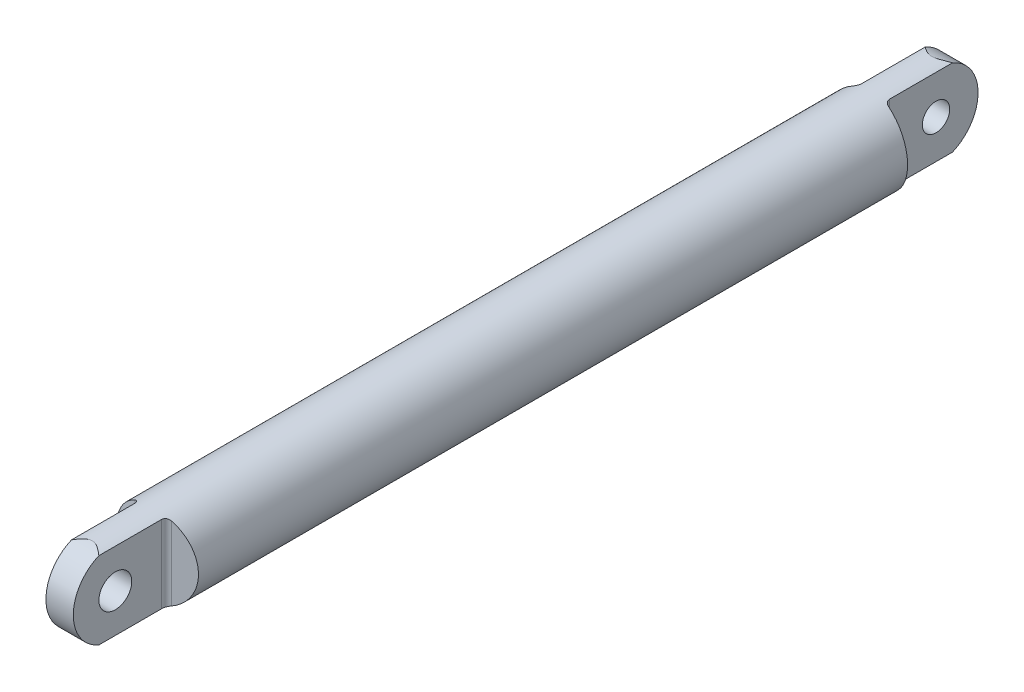
SolidWorks part; units mm, degrees
material "AISI 1045 Steel, cold drawn"
ref_plane "Front Plane" through (0, 0, 0) normal (0, 0, 1) x (1, 0, 0)
ref_plane "Top Plane" through (0, 0, 0) normal (0, 1, 0) x (1, 0, 0)
ref_plane "Right Plane" through (0, 0, 0) normal (1, 0, 0) x (0, 0, -1)
sketch "Sketch1" plane through (0, 0, 0) normal (0, 0, 1) x (1, 0, 0)
  circle A0 centre (0, 0) radius 7.5
  dimension "D1" = 15
extrude "Boss-Extrude1" add sketch "Sketch1" along normal mid plane 165.37
sketch "Sketch6" plane through (0, 0, 0) normal (1, 0, 0) x (0, 0, -1)
  line L1 (82.685, 7.5) -> (-82.685, 7.5) construction
  line L8 (82.685, 7.5) -> (82.685, -7.5)
  line L10 (76.685, -7.5) -> (82.685, -7.5)
  line L13 (82.685, 7.5) -> (76.685, 7.5)
  line L15 (82.685, 7.5) -> (-82.685, 7.5) construction
  arc A1 (76.685, -7.5) -> (76.685, 7.5) centre (74.9975, 0) ccw
  dimension "D1" = 6
extrude "Cut-Extrude2" cut sketch "Sketch6" against normal through all and the other way through all
sketch "Sketch7" plane through (0, 0, 0) normal (0, 1, 0) x (1, 0, 0)
  line L0 (-2.5, 82.685) -> (-2.5, 65.685)
  line L4 (-7.5, 82.685) -> (-7.5, -82.685) construction
  line L5 (-7.5, 64.8034) -> (-7.5, 82.685)
  line L6 (-7.5, 82.685) -> (-2.5, 82.685)
  line L7 (0, 3.0864) -> (0, -9.0403) construction
  line L8 (7.5, 82.685) -> (2.5, 82.685)
  line L9 (2.5, 82.685) -> (2.5, 65.685)
  line L16 (-7.5, 64.8034) -> (-2.5, 65.685)
  line L21 (2.5, 65.685) -> (7.5, 64.8034)
  line L22 (7.5, -82.685) -> (7.5, 82.685) construction
  line L23 (7.5, 64.8034) -> (7.5, 82.685)
  dimension "D3" = 100
  dimension "D2" = 17
  dimension "D1" = 2.5
  dimension "D4" = 100
  dimension "D5" = 2.5
extrude "Cut-Extrude3" cut sketch "Sketch7" against normal through all both and the other way through all
sketch "Sketch8" plane through (-2.5, 0, 0) normal (1, 0, 0) x (0, 0, -1)
  circle A0 centre (74.9975, 0) radius 2.5
  arc A7 (78.0137, -7.0711) -> (78.0137, 7.0711) centre (74.9975, 0) ccw construction
  dimension "D1" = 5
extrude "Cut-Extrude4" cut sketch "Sketch8" against normal through all both and the other way through all contours A0
fillet "Fillet1" radius 1 2 edges at (-2.5, 0, -65.685) (2.5, 0, -65.685)
mirror "Mirror2" about plane through (0, 0, 0) normal (0, 0, 1) of "Cut-Extrude2", "Cut-Extrude3", "Fillet1"
sketch "Sketch9" plane through (2.5, 0, 0) normal (1, 0, 0) x (0, 0, -1)
  circle A0 centre (-74.9975, 0) radius 3
  arc A1 (-78.0137, 7.0711) -> (-78.0137, -7.0711) centre (-74.9975, 0) ccw construction
  dimension "D1" = 6
extrude "Cut-Extrude5" cut sketch "Sketch9" against normal blind 10
equation "\"D4@Sketch7\"=\"D3@Sketch7\""
